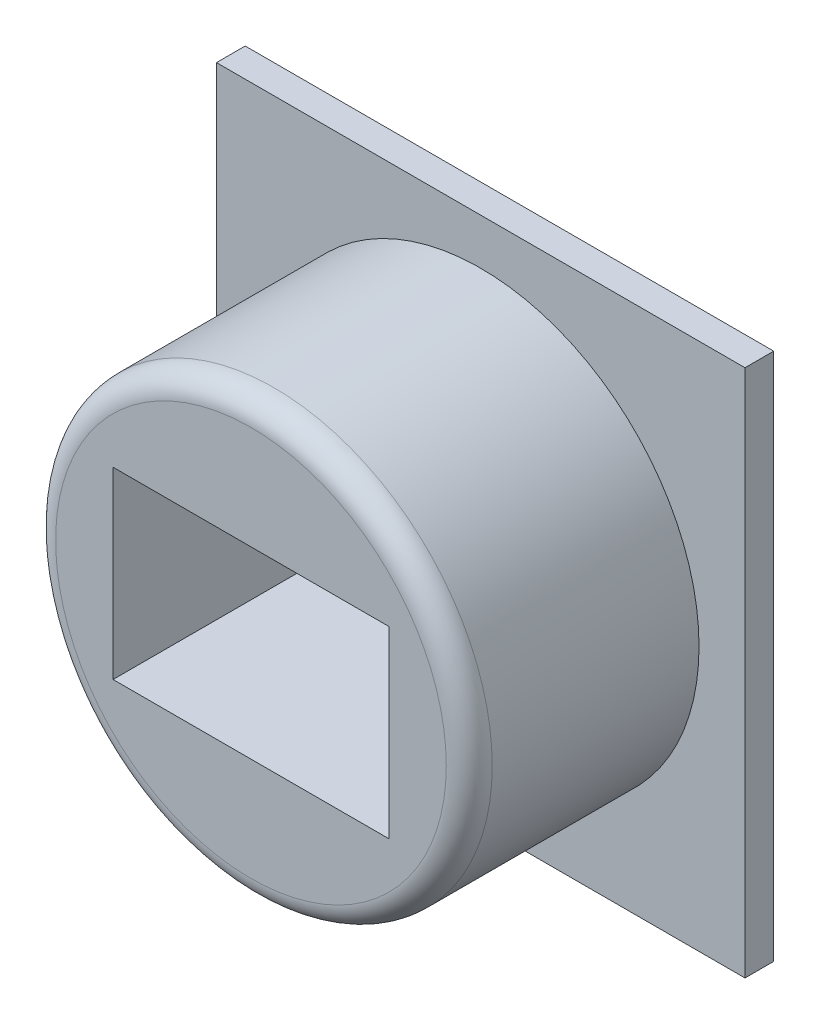
SolidWorks part; units mm, degrees
ref_plane "Спереди" through (0, 0, 0) normal (0, 0, 1) x (1, 0, 0)
ref_plane "Сверху" through (0, 0, 0) normal (0, 1, 0) x (1, 0, 0)
ref_plane "Справа" through (0, 0, 0) normal (1, 0, 0) x (0, 0, -1)
sketch "Эскиз1" plane through (0, 0, 0) normal (0, 0, 1) x (1, 0, 0)
  circle A0 centre (0, 0) radius 3.8
  dimension "D1" = 7.6
extrude "Бобышка-Вытянуть1" add sketch "Эскиз1" along normal blind 4
sketch "Эскиз2" plane through (0, 0, 0) normal (0, 0, -1) x (-1, 0, 0)
  line L1 (-4.6, 4.6) -> (4.6, 4.6)
  line L2 (-4.6, 4.6) -> (-4.6, -4.6)
  line L3 (-4.6, -4.6) -> (4.6, -4.6)
  line L4 (4.6, 4.6) -> (4.6, -4.6)
  circle A0 centre (0, 0) radius 3.8 construction
  dimension "D1" = 4.6
  dimension "D2" = 4.6
  dimension "D3" = 4.6
  dimension "D4" = 4.6
extrude "Бобышка-Вытянуть2" add sketch "Эскиз2" along normal blind 0.5
fillet "Скругление1" radius 0.4 1 edges at (3.8, 0, 4)
sketch "Эскиз4" plane through (0, 0, 4) normal (0, 0, 1) x (1, 0, 0)
  line L1 (-2.4, 1.6) -> (2.4, 1.6)
  line L2 (-2.4, 1.6) -> (-2.4, -1.6)
  line L3 (-2.4, -1.6) -> (2.4, -1.6)
  line L4 (2.4, 1.6) -> (2.4, -1.6)
  circle A0 centre (0, 0) radius 3.4 construction
  dimension "D1" = 1.6
  dimension "D2" = 2.4
  dimension "D3" = 2.4
  dimension "D4" = 1.6
extrude "Вырез-Вытянуть1" cut sketch "Эскиз4" against normal blind 4
sketch "Эскиз5" plane through (0, 0, 0) normal (0, 0, 1) x (1, 0, 0)
  circle A0 centre (0, 0) radius 0.6
  dimension "D1" = 1.2
extrude "Вырез-Вытянуть2" cut sketch "Эскиз5" against normal through all
